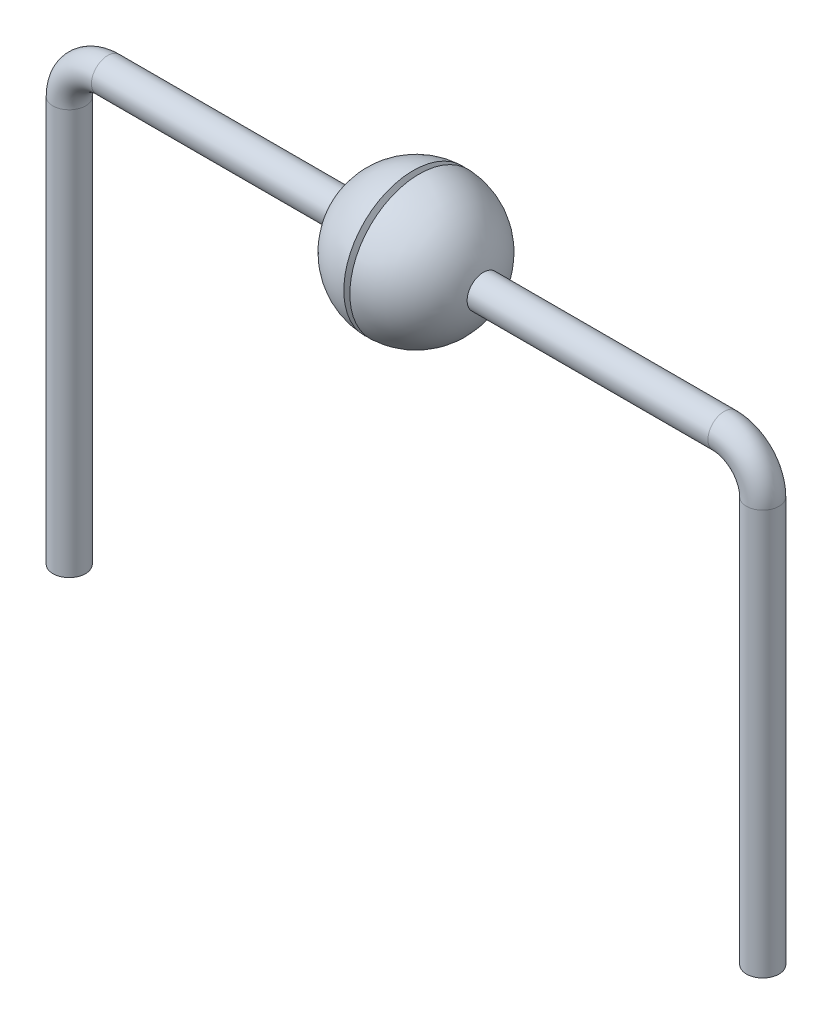
SolidWorks part; units mm, degrees
ref_plane "Спереди" through (0, 0, 0) normal (0, 0, 1) x (1, 0, 0)
ref_plane "Сверху" through (0, 0, 0) normal (0, 1, 0) x (1, 0, 0)
ref_plane "Справа" through (0, 0, 0) normal (1, 0, 0) x (0, 0, -1)
sketch "Эскиз1" plane through (0, 0, 0) normal (0, 1, 0) x (1, 0, 0)
  line L0 (-29.7512, 0) -> (31.712, 0) construction
  line L1 (-1.7496, 0.4231) -> (-1.7496, 0)
  line L2 (-1.7496, 0) -> (1.7496, 0)
  line L4 (1.7496, 0) -> (1.7496, 0.4231)
  line L5 (-0.0758, 1.7984) -> (0, 1.6459)
  line L6 (0, 1.6459) -> (0.081, 1.7982)
  line L7 (0, 1.6459) -> (0, -0.8803) construction
  arc A0 (0.081, 1.7982) -> (1.7496, 0.4231) centre (0, 0) cw
  arc A1 (-1.7496, 0.4231) -> (-0.0758, 1.7984) centre (0, 0) cw
revolve "Повернуть2" add sketch "Эскиз1" angle 360 about L0
sketch "Эскиз2" plane through (0, 0, 0) normal (0, 0, 1) x (1, 0, 0)
  line L0 (0, 0) -> (-8, 0)
  line L1 (-9, -1) -> (-9, -11.5149)
  arc A1 (-8, 0) -> (-9, -1) centre (-8, -1) ccw
  point P2 (0, 0)
  point P3 (0, 0)
  dimension "D2" = 9
sketch "Эскиз3" plane through (-1.7496, 0, 0) normal (-1, 0, 0) x (0, 0, 1)
  circle A0 centre (0, 0) radius 0.4231
sweep "По траектории1" add profiles "Эскиз3" path "Эскиз2"
mirror "Зеркальное отражение1" about plane through (0, 0, 0) normal (1, 0, 0) of "По траектории1"
